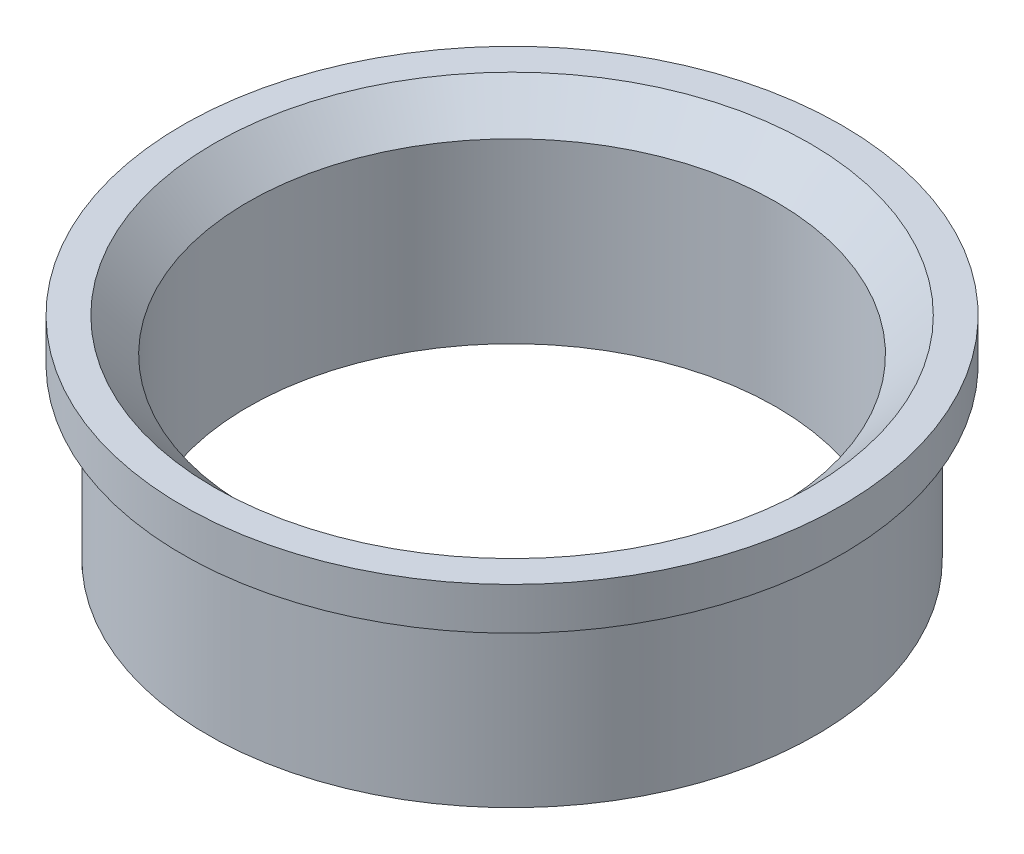
SolidWorks part; units mm, degrees
ref_plane "Front Plane" through (0, 0, 0) normal (0, 0, 1) x (1, 0, 0)
ref_plane "Top Plane" through (0, 0, 0) normal (0, 1, 0) x (1, 0, 0)
ref_plane "Right Plane" through (0, 0, 0) normal (1, 0, 0) x (0, 0, -1)
sketch "Sketch2" plane through (0, 0, 0) normal (0, 0, 1) x (1, 0, 0)
  line L0 (156.686, 0) -> (0, 0) construction
  line L1 (0, 0) -> (0, 175.5814) construction
  line L2 (72, 0) -> (72, 40)
  line L3 (72, 40) -> (78, 40)
  line L4 (78, 40) -> (78, 50)
  line L5 (78, 50) -> (70.5, 50)
  line L6 (70.5, 50) -> (62.5, 42)
  line L7 (62.5, 42) -> (62.5, 0)
  line L8 (62.5, 0) -> (72, 0)
  dimension "D1" = 62.5
  dimension "D2" = 72
  dimension "D3" = 78
  dimension "D4" = 8
  dimension "D5" = 135
  dimension "D6" = 10
  dimension "D7" = 40
revolve "Revolve1" add sketch "Sketch2" angle 360 about L1
